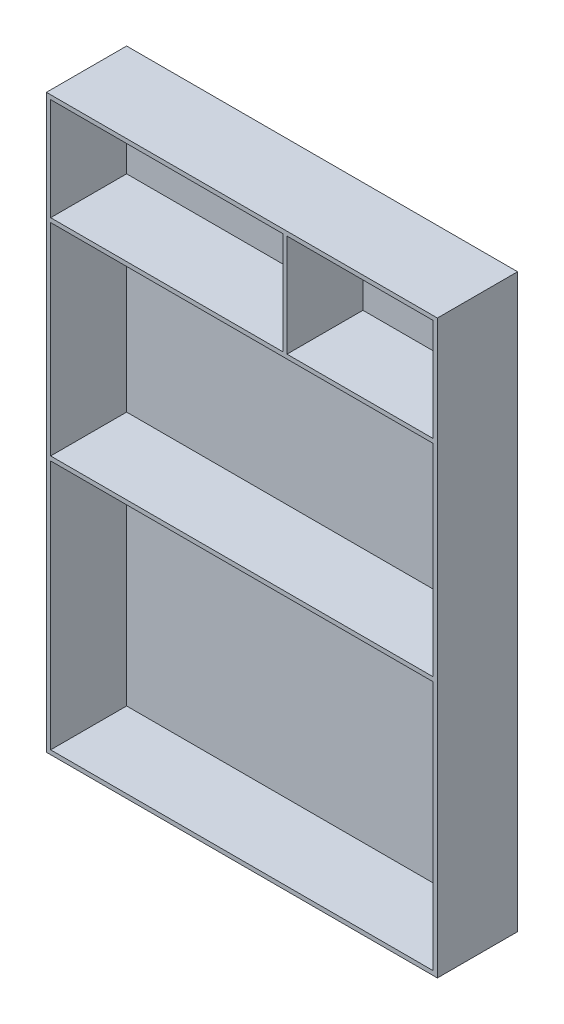
SolidWorks part; units mm, degrees
material "Custom Plastic"
ref_plane "X-Y Datum" through (0, 0, 0) normal (0, 0, 1) x (1, 0, 0)
ref_plane "X-Z Datum" through (0, 0, 0) normal (0, 1, 0) x (1, 0, 0)
ref_plane "Y-Z Datum" through (0, 0, 0) normal (1, 0, 0) x (0, 0, -1)
sketch "Sketch1" plane through (0, 0, 0) normal (0, 0, 1) x (1, 0, 0)
  line L0 (-94.6022, -110.7569) -> (98.0976, -110.7569) construction
  line L1 (-94.6022, -110.7569) -> (-94.6022, 26.7476) construction
  line L2 (-94.6022, 26.7476) -> (98.0976, 26.7476) construction
  line L3 (98.0976, -110.7569) -> (98.0976, 26.7476) construction
  line L4 (-94.6022, 26.7476) -> (-137.5735, 26.7476) construction
  line L5 (-94.6022, 26.7476) -> (-94.6022, -110.7569) construction
  line L6 (-94.6022, -110.7569) -> (-137.5735, -110.7569) construction
  line L7 (-137.5735, 26.7476) -> (-137.5735, -110.7569) construction
  line L8 (135.6209, -122.6228) -> (135.6209, -110.5186) construction
  line L9 (-84.9188, 31.8276) -> (-84.9188, 150.9335) construction
  line L10 (-84.9188, 31.8276) -> (123.5166, 31.8276) construction
  line L11 (123.5166, 31.8276) -> (123.5166, 150.9335) construction
  line L12 (-84.9188, 150.9335) -> (123.5166, 150.9335) construction
  line L14 (135.6209, -122.6228) -> (-94.6022, -122.6228)
  line L15 (135.6209, -122.6228) -> (135.6209, 216.2965)
  line L16 (135.6209, 216.2965) -> (-94.6022, 216.2965)
  line L17 (-94.6022, -122.6228) -> (-94.6022, 216.2965)
  circle A0 centre (-82.9821, 15.1275) radius 4.003 construction
  circle A1 centre (87.4459, 17.0641) radius 4.003 construction
  circle A2 centre (87.099, -99.1349) radius 4.003 construction
  circle A3 centre (-84.9188, -101.0734) radius 4.003 construction
  circle A4 centre (-75.7196, 40.8815) radius 4.003 construction
  circle A5 centre (-75.7558, 140.1326) radius 4.003 construction
  circle A6 centre (114.3174, 139.8944) radius 4.003 construction
  circle A7 centre (114.3174, 40.8815) radius 4.003 construction
  dimension "D1" = 5.08
extrude "Boss-Extrude1" add sketch "Sketch1" along normal blind 45.72
shell "Shell1" thickness 2.54
sketch "Sketch2" plane through (0, 0, 0) normal (0, 0, 1) x (1, 0, 0)
  line L1 (45.0978, 154.7435) -> (-94.6022, 154.7435)
  line L2 (135.6209, -122.6228) -> (135.6209, 216.2965) construction
  line L14 (-84.9188, 31.8276) -> (-84.9188, 26.7476) construction
  line L15 (-94.6022, 26.7476) -> (98.0976, 26.7476) construction
  line L16 (-94.6022, 29.2356) -> (-94.6022, 30.5576)
  line L17 (-94.6022, -122.6228) -> (-94.6022, 216.2965) construction
  line L18 (-94.6022, 29.2356) -> (-94.6022, 27.9656)
  line L19 (-94.6022, 30.5576) -> (135.6209, 30.5576)
  line L20 (-94.6022, 27.9656) -> (135.6209, 27.9656)
  line L21 (135.6209, 27.9656) -> (135.6209, 30.5576)
  line L22 (135.6209, 216.2965) -> (-94.6022, 216.2965) construction
  line L23 (45.0978, 216.2965) -> (45.0978, 154.7435)
  line L26 (47.6378, 154.7435) -> (47.6378, 216.2965)
  line L27 (47.6378, 216.2965) -> (45.0978, 216.2965)
  line L28 (-84.9188, 152.2035) -> (135.6209, 152.2035)
  line L29 (135.6209, 152.2035) -> (135.6209, 154.7435)
  line L30 (135.6209, 154.7435) -> (47.6378, 154.7435)
  line L31 (-94.6022, 154.7435) -> (-94.6022, 152.2035)
  line L32 (-94.6022, 152.2035) -> (-84.9188, 152.2035)
extrude "Boss-Extrude2" add sketch "Sketch2" along normal up to surface (45.72 mm away) up to face at (20.5093, 46.8368, 45.72)
